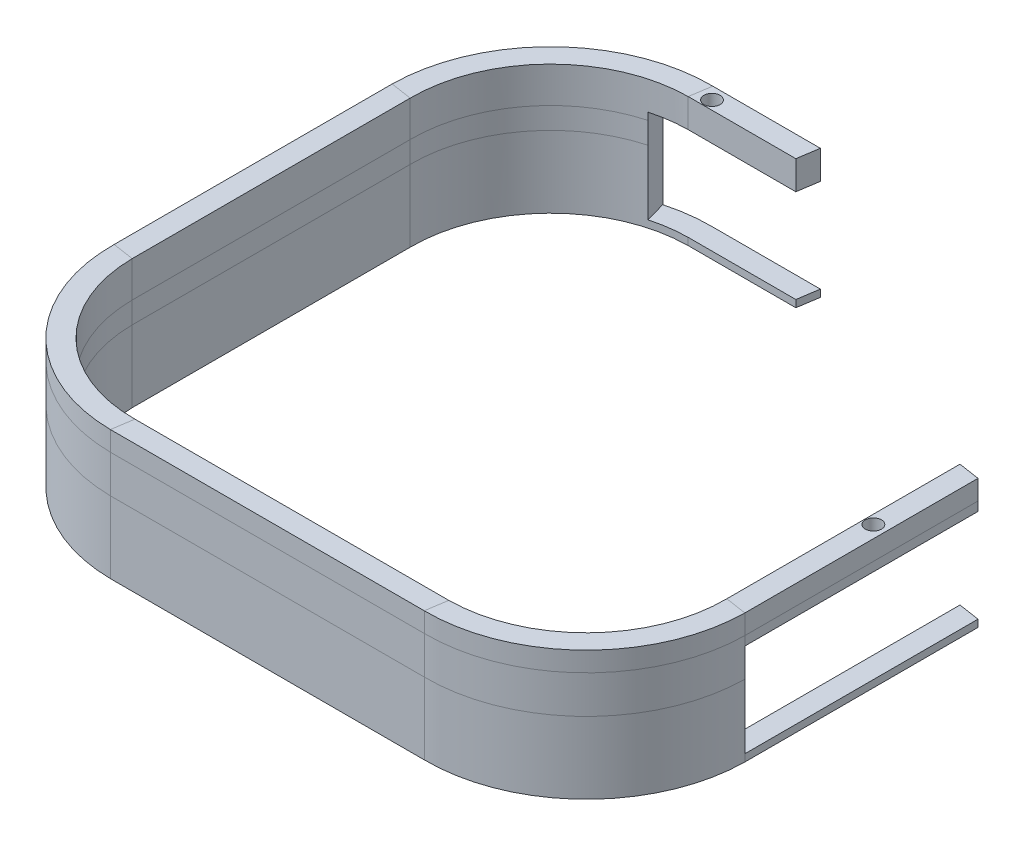
SolidWorks part; units mm, degrees
ref_plane "Front Plane" through (0, 0, 0) normal (0, 0, 1) x (1, 0, 0)
ref_plane "Top Plane" through (0, 0, 0) normal (0, 1, 0) x (1, 0, 0)
ref_plane "Right Plane" through (0, 0, 0) normal (1, 0, 0) x (0, 0, -1)
ref_plane "Plane1" through (0, 152.6876, 0) normal (0, 1, 0) x (1, 0, 0)
sketch "Sketch1" plane through (0, 152.6876, 0) normal (0, 1, 0) x (1, 0, 0)
  line L0 (-16.3663, 42.6705) -> (-87.6163, 42.6705) construction
  line L1 (-87.6163, -76.0795) -> (-87.6163, -117.3295) construction
  line L2 (-87.6163, -117.3295) -> (-46.3663, -117.3295) construction
  line L3 (82.3837, -117.3295) -> (82.3837, -11.0795) construction
  line L4 (-44.8663, 42.6705) -> (-16.3663, 42.6705) construction
  line L5 (82.3837, -11.0795) -> (82.3837, -39.5795) construction
  line L6 (-87.6163, 1.4205) -> (-87.6163, -76.0795)
  line L7 (-87.6163, 1.4205) -> (-87.6163, 42.6705) construction
  line L8 (-46.3663, -117.3295) -> (41.1337, -117.3295)
  line L9 (82.3837, -76.0795) -> (82.3837, -11.0795)
  line L10 (-46.3663, 42.6705) -> (-16.3663, 42.6705)
  line L11 (41.1337, -117.3295) -> (82.3837, -117.3295) construction
  circle A0 centre (-42.6163, 42.6705) radius 2.25 construction
  circle A1 centre (82.3837, -37.3295) radius 2.25 construction
  arc A2 (-46.3663, 42.6705) -> (-87.6163, 1.4205) centre (-46.3663, 1.4205) ccw
  arc A3 (-87.6163, -76.0795) -> (-46.3663, -117.3295) centre (-46.3663, -76.0795) ccw
  arc A4 (41.1337, -117.3295) -> (82.3837, -76.0795) centre (41.1337, -76.0795) ccw
  circle A5 centre (-22.6163, 42.6705) radius 2.25 construction
  circle A6 centre (82.3837, -17.3295) radius 2.25 construction
  dimension "D3" = 4
  dimension "D1" = 160
  dimension "D2" = 170
  dimension "D4" = 4
  dimension "D5" = 30
sketch "Sketch2" plane through (-52.6163, 0, 0) normal (-1, 0, 0) x (0, 0, 1)
  line L0 (-42.6705, 158.6876) -> (-42.6705, 147.9297) construction
  line L3 (-45.6705, 153.2117) -> (-45.6705, 158.6876)
  line L4 (-45.6705, 158.6876) -> (-39.6705, 158.6876)
  line L5 (-39.6705, 148.6876) -> (-39.6705, 158.6876)
  line L8 (-45.6705, 142.6876) -> (-45.6705, 122.6876)
  line L9 (-45.6705, 122.6876) -> (-39.6705, 122.6876)
  line L10 (-39.6705, 142.6876) -> (-39.6705, 122.6876)
  line L12 (-42.6705, 152.6876) -> (-42.6705, 147.9297) construction
  line L13 (-1.4205, 152.6876) -> (-42.6705, 152.6876) construction
  line L14 (-45.6705, 153.2117) -> (-45.6705, 142.6876)
  line L15 (-1.4205, 152.6876) -> (-42.6705, 152.6876) construction
  line L16 (-12.6705, 148.6876) -> (-242.6705, 148.6876) construction
  line L18 (-39.6705, 148.6876) -> (-39.6705, 142.6876)
  dimension "D1" = 6
  dimension "D2" = 10
  dimension "D3" = 20
  dimension "D4" = 36
  dimension "D5" = 10
sweep "Sweep1" add profiles "Sketch2" path "Sketch1"
sketch "Sketch4" plane through (0, 146.6876, 0) normal (0, -1, 0) x (1, 0, 0)
  circle A2 centre (-42.6163, -42.6705) radius 2.25 construction
  circle A3 centre (82.3837, 37.3295) radius 2.25 construction
  point P0 (-42.6163, -42.6705)
  point P1 (82.3837, 37.3295)
  point P11 (-42.6163, -42.6705)
  point P14 (82.3837, 37.3295)
hole_wizard "M4 Clearance Hole1" positions "Sketch4" profile "Sketch6" hole size "M4" standard "ANSI Metric"
sketch "Sketch6" plane through (-42.6163, 146.6876, -42.6705) normal (1, 0, 0) x (0, 0, -1)
  line L0 (0, 0) -> (0, 12)
  line L1 (0, 12) -> (2.25, 12)
  line L2 (2.25, 12) -> (2.25, 0)
  line L5 (2.25, 0) -> (0, 0)
  line L11 (0, -6.35) -> (0, 107.95) construction
  dimension "Thru Hole Dia." = 4.5
  dimension "Thru Hole Depth" = 12
sketch "Sketch7" plane through (0, 148.6876, 0) normal (0, 1, 0) x (1, 0, 0)
  line L0 (79.889, -75.6971) -> (79.889, -10.6971) construction
  line L1 (79.889, -10.6971) -> (85.8198, -11.6062) construction
  line L2 (85.8198, -11.6062) -> (85.8198, -76.6062) construction
  line L3 (85.8198, -76.6062) -> (79.889, -75.6971) construction
  line L4 (-16.7487, 40.1759) -> (-46.7487, 40.1759) construction
  line L6 (-45.8396, 46.1066) -> (-15.8396, 46.1066) construction
  line L7 (-15.8396, 46.1066) -> (-16.7487, 40.1759) construction
  line L8 (79.889, -75.6971) -> (79.889, -10.6971)
  line L9 (79.889, -10.6971) -> (85.8198, -11.6062)
  line L10 (85.8198, -11.6062) -> (85.8198, -76.6062)
  line L11 (85.8198, -76.6062) -> (79.889, -75.6971)
  line L12 (-16.7487, 40.1759) -> (-46.7487, 40.1759)
  line L14 (-45.8396, 46.1066) -> (-15.8396, 46.1066)
  line L15 (-15.8396, 46.1066) -> (-16.7487, 40.1759)
  line L16 (85.8198, -51.3295) -> (79.889, -51.3295)
  line L17 (102.3837, -47.3295) -> (242.3837, -47.3295) construction
  line L18 (-45.8396, 46.1066) -> (-56.6163, 46.1066) construction
  line L19 (-56.6163, 46.1066) -> (-56.6163, 40.1759) construction
  line L20 (-56.6163, 40.1759) -> (-46.7487, 40.1759) construction
  line L21 (-52.6163, -47.3295) -> (-52.6163, 302.6705) construction
  line L22 (-45.8396, 46.1066) -> (-56.6163, 46.1066) construction
  line L23 (-56.6163, 38.7978) -> (-58.1852, 44.5185)
  line L25 (-91.0524, 1.9472) -> (-85.1217, 1.0381)
  line L26 (-46.7487, 40.1759) -> (-45.8396, 46.1066)
  arc A2 (-45.8396, 46.1066) -> (-91.0524, 1.9472) centre (-46.3663, 1.4205) ccw
  arc A3 (-46.7487, 40.1759) -> (-85.1217, 1.0381) centre (-46.3663, 1.4205) ccw
  arc A4 (-45.8396, 46.1066) -> (-58.1852, 44.5185) centre (-46.3663, 1.4205) ccw
  arc A5 (-46.7487, 40.1759) -> (-56.6163, 38.7978) centre (-46.3663, 1.4205) ccw
  dimension "D1" = 4
  dimension "D2" = 4
  dimension "D3" = 0
extrude "Cut-Extrude1" cut sketch "Sketch7" against normal offset from surface (26 mm away) 2 from offset 2
